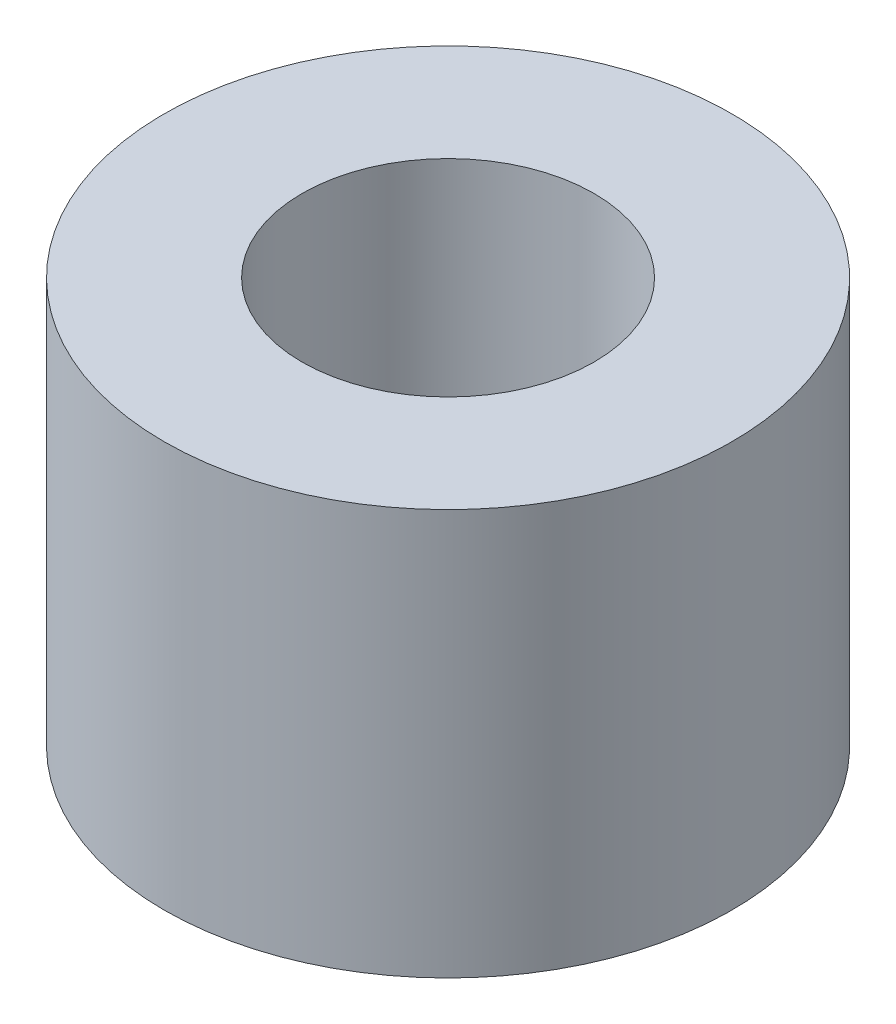
SolidWorks part; units mm, degrees
ref_plane "Front Plane" through (0, 0, 0) normal (0, 0, 1) x (1, 0, 0)
ref_plane "Top Plane" through (0, 0, 0) normal (0, 1, 0) x (1, 0, 0)
ref_plane "Right Plane" through (0, 0, 0) normal (1, 0, 0) x (0, 0, -1)
sketch "Sketch1" plane through (0, 0, 0) normal (0, 1, 0) x (1, 0, 0)
  circle A0 centre (0, 0) radius 3.5
  circle A1 centre (0, 0) radius 1.8
  dimension "D1" = 7
  dimension "D2" = 3.6
extrude "Boss-Extrude1" add sketch "Sketch1" along normal blind 5
